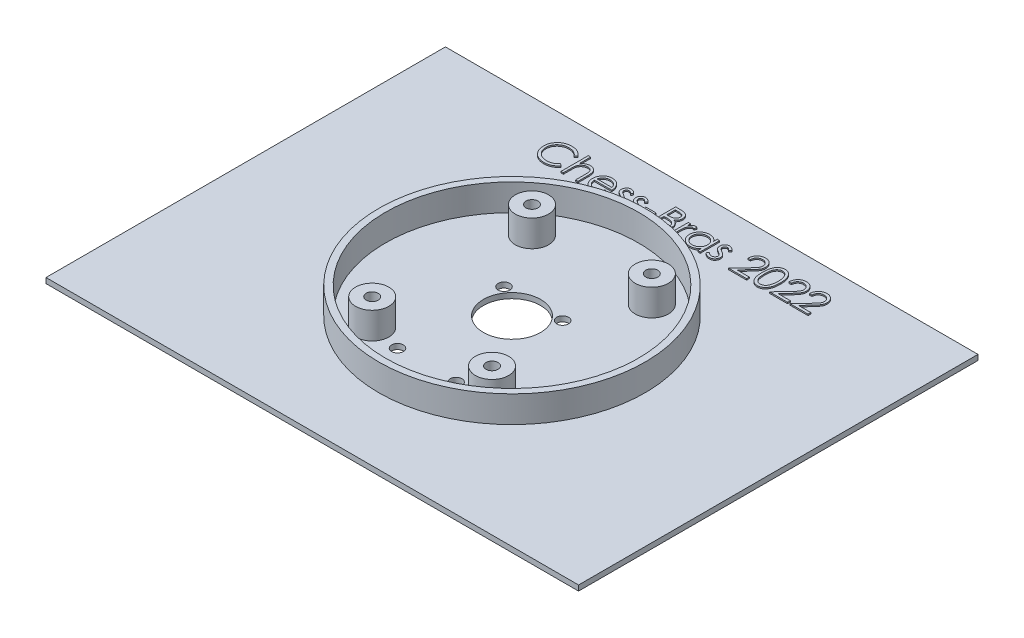
SolidWorks part; units mm, degrees
ref_plane "Plan de face" through (0, 0, 0) normal (0, 0, 1) x (1, 0, 0)
ref_plane "Plan de dessus" through (0, 0, 0) normal (0, 1, 0) x (1, 0, 0)
ref_plane "Plan de droite" through (0, 0, 0) normal (1, 0, 0) x (0, 0, -1)
sketch "Esquisse1" plane through (0, 0, 0) normal (0, 1, 0) x (1, 0, 0)
  line L1 (-90, -90) -> (90, -90) construction
  line L2 (-90, -90) -> (-90, 90) construction
  line L3 (-90, 90) -> (90, 90) construction
  line L4 (90, -90) -> (90, 90) construction
  line L5 (-90, -90) -> (90, 90) construction
  line L6 (-90, 90) -> (90, -90) construction
  point P0 (0, 0)
  dimension "D1" = 180
  dimension "D2" = 180
sketch "Esquisse2" plane through (0, 0, 0) normal (0, 1, 0) x (1, 0, 0)
  line L1 (-100, -75) -> (100, -75)
  line L2 (-100, -75) -> (-100, 75)
  line L3 (-100, 75) -> (100, 75)
  line L4 (100, -75) -> (100, 75)
  line L5 (-100, -75) -> (100, 75) construction
  line L6 (-100, 75) -> (100, -75) construction
  point P0 (0, 0)
  dimension "D1" = 200
  dimension "D2" = 150
extrude "Boss.-Extru.1" add sketch "Esquisse2" along normal blind 1
sketch "Esquisse3" plane through (0, 1, 0) normal (0, 1, 0) x (1, 0, 0)
  line L4 (100, -75) -> (100, 75)
  line L5 (100, 75) -> (-100, 75)
  line L6 (-100, 75) -> (-100, -75)
  line L7 (-100, -75) -> (100, -75)
  line L8 (100, -75) -> (100, 75)
  line L9 (100, 75) -> (-100, 75)
  line L10 (-100, 75) -> (-100, -75)
  line L11 (-100, -75) -> (100, -75)
  line L12 (7.5, 59.5294) -> (7.5, 65)
  line L13 (90, 65) -> (7.5, 65)
  line L16 (-90, 65) -> (-90, 7.5)
  line L17 (-90, -65) -> (-7.5, -65)
  line L18 (90, -65) -> (90, -7.5)
  line L19 (0, 42.5) -> (0, 65) construction
  line L20 (-7.5, 59.5294) -> (-7.5, 65)
  line L39 (-7.5, 42.5) -> (-7.5, 65) construction
  line L40 (7.5, 42.5) -> (7.5, 65) construction
  line L41 (-90, 0) -> (90, 0) construction
  line L42 (-7.5, 65) -> (-90, 65)
  line L43 (90, 65) -> (-90, 65) construction
  line L45 (-90, -7.5) -> (-59.5294, -7.5)
  line L46 (-90, 7.5) -> (-59.5294, 7.5)
  line L47 (-90, -7.5) -> (-90, -65)
  line L48 (-90, 65) -> (-90, -65) construction
  line L51 (-90, 7.5) -> (90, 7.5) construction
  line L52 (59.5294, -7.5) -> (90, -7.5)
  line L53 (-90, -7.5) -> (90, -7.5) construction
  line L54 (59.5294, 7.5) -> (90, 7.5)
  line L55 (90, 7.5) -> (90, 65)
  line L56 (90, -65) -> (90, 65) construction
  line L57 (0, 0) -> (0, -75) construction
  line L58 (-7.5, -59.5294) -> (-7.5, -65)
  line L59 (7.5, -65) -> (90, -65)
  line L60 (-7.5, 0) -> (-7.5, -75) construction
  line L62 (7.5, -59.5294) -> (7.5, -65)
  line L63 (-90, -65) -> (90, -65) construction
  arc A0 (59.5294, 7.5) -> (7.5, 59.5294) centre (0, 0) ccw
  arc A1 (-7.5, 59.5294) -> (-59.5294, 7.5) centre (0, 0) ccw
  arc A2 (-59.5294, -7.5) -> (-7.5, -59.5294) centre (0, 0) ccw
  arc A3 (7.5, -59.5294) -> (59.5294, -7.5) centre (0, 0) ccw
  point P8 (0, 0)
  point P39 (0, 0)
  dimension "D10" = 120
  dimension "D5" = 7.5
  dimension "D6" = 7.5
  dimension "D9" = 0
  dimension "D1" = 0
  dimension "D2" = 10
  dimension "D7" = 7.5
  dimension "D8" = 7.5
extrude "Boss.-Extru.2" add sketch "Esquisse3" along normal blind 1
sketch "Esquisse21" plane through (0, 2, 0) normal (0, 1, 0) x (1, 0, 0)
  line L0 (0, 38.0247) -> (0, -27.9888) construction
  line L1 (31.0483, 0) -> (-33.3119, 0) construction
  circle A0 centre (-22.5, 30) radius 6.25
  circle A1 centre (-22.5, -30) radius 6.25
  circle A3 centre (22.5, 30) radius 6.25
  circle A5 centre (22.5, -30) radius 6.25
  dimension "D3" = 12.5
  dimension "D1" = 22.5
  dimension "D2" = 30
extrude "Boss.-Extru.6" add sketch "Esquisse21" along normal blind 10
hole_wizard "Chambrage pour vis à tête cylindrique à 6 pans creux (ou vis CHC) M21" positions "Esquisse7" profile "Esquisse8" counterbore size "M2" standard "Ansi Metric" end condition through all
sketch "Esquisse7" plane through (0, 0, 0) normal (0, -1, 0) x (-1, 0, 0)
  line L0 (-19.1786, -12) -> (19.1786, -12) construction
  line L2 (0, -21.3375) -> (0, 18.8747) construction
  point P9 (-11, -32)
  point P22 (11, -32)
  point P24 (-11, 8)
  point P25 (11, 8)
  point P26 (0, -12)
  dimension "D1" = 11
  dimension "D2" = 20
  dimension "D3" = 8
sketch "Esquisse8" plane through (-11, 0, -8) normal (1, 0, 0) x (0, 0, -1)
  line L0 (0, 0) -> (0, 12)
  line L1 (0, 12) -> (1.2, 12)
  line L3 (1.2, 12) -> (1.2, 3.5)
  line L4 (1.2, 3.5) -> (2.2, 3.5)
  line L5 (2.2, 3.5) -> (2.2, 0)
  line L7 (2.2, 0) -> (0, 0)
  line L11 (0, -6.35) -> (0, 107.95) construction
  dimension "Diamètre du perçage jusqu'au prochain" = 2.4
  dimension "Profondeur du perçage jusqu'au prochain" = 12
  dimension "Diamètre du chambrage" = 4.4
  dimension "Profondeur du chambrage" = 3.5
hole_wizard "Chambrage pour vis à tête cylindrique à 6 pans creux (ou vis CHC) M41" positions "Esquisse12" profile "Esquisse13" counterbore size "M4" standard "Ansi Metric" end condition through all
sketch "Esquisse12" plane through (0, 0, 0) normal (0, -1, 0) x (-1, 0, 0)
  line L0 (-30.249, 0) -> (45.5995, 0) construction
  line L2 (0, 38.4688) -> (0, -28.5023) construction
  point P0 (22.5, 30)
  point P4 (22.5, -30)
  point P17 (-22.5, 30)
  point P19 (-22.5, -30)
  dimension "D1" = 22.5
  dimension "D2" = 30
sketch "Esquisse13" plane through (-22.5, 0, -30) normal (1, 0, 0) x (0, 0, -1)
  line L0 (0, 0) -> (0, 12)
  line L1 (0, 12) -> (2.25, 12)
  line L3 (2.25, 12) -> (2.25, 5)
  line L4 (2.25, 5) -> (4, 5)
  line L5 (4, 5) -> (4, 0)
  line L7 (4, 0) -> (0, 0)
  line L11 (0, -6.35) -> (0, 107.95) construction
  dimension "Diamètre du perçage jusqu'au prochain" = 4.5
  dimension "Profondeur du perçage jusqu'au prochain" = 12
  dimension "Diamètre du chambrage" = 8
  dimension "Profondeur du chambrage" = 5
sketch "Esquisse15" plane through (0, 2, 0) normal (0, 1, 0) x (1, 0, 0)
  circle A0 centre (0, 0) radius 10.75
  dimension "D1" = 21.5
extrude "Enlèv. mat.-Extru.2" cut sketch "Esquisse15" against normal through all
sketch "Esquisse22" plane through (0, 2, 0) normal (0, 1, 0) x (1, 0, 0)
  circle A0 centre (0, 0) radius 50
  circle A1 centre (0, 0) radius 47.5
  dimension "D1" = 100
  dimension "D2" = 95
extrude "Boss.-Extru.7" add sketch "Esquisse22" along normal blind 10
sketch "Esquisse23" plane through (0, 1, 0) normal (0, 1, 0) x (1, 0, 0)
  line L0 (-90, -7.5) -> (-59.5294, -7.5)
  line L1 (-7.5, -59.5294) -> (-7.5, -65)
  line L2 (-7.5, -65) -> (-90, -65)
  line L3 (-90, -65) -> (-90, -7.5)
  line L4 (7.5, -59.5294) -> (7.5, -65)
  line L5 (7.5, -65) -> (90, -65)
  line L6 (90, -65) -> (90, -7.5)
  line L7 (90, -7.5) -> (59.5294, -7.5)
  line L8 (-7.5, 59.5294) -> (-7.5, 65)
  line L9 (-7.5, 65) -> (-90, 65)
  line L10 (-90, 65) -> (-90, 7.5)
  line L11 (-90, 7.5) -> (-59.5294, 7.5)
  line L12 (7.5, 59.5294) -> (7.5, 65)
  line L13 (7.5, 65) -> (90, 65)
  line L14 (90, 65) -> (90, 7.5)
  line L15 (90, 7.5) -> (59.5294, 7.5)
  arc A0 (-59.5294, -7.5) -> (-7.5, -59.5294) centre (0, 0) ccw
  arc A1 (59.5294, -7.5) -> (7.5, -59.5294) centre (0, 0) cw
  arc A2 (-59.5294, 7.5) -> (-7.5, 59.5294) centre (0, 0) cw
  arc A3 (59.5294, 7.5) -> (7.5, 59.5294) centre (0, 0) ccw construction
  arc A6 (7.5, 59.5294) -> (59.5294, 7.5) centre (0, 0) cw
  point P45 (7.5, 7.7015)
  point P46 (7.5, 7.5)
  point P47 (7.5, 7.5)
  point P48 (0, 0)
  point P49 (59.5294, 7.5)
  point P50 (4.957, 4.957)
  point P51 (4.957, 4.957)
  point P52 (0, 0)
extrude "Boss.-Extru.8" add sketch "Esquisse23" along normal blind 1
sketch "Esquisse24" plane through (0, 2, 0) normal (0, 1, 0) x (1, 0, 0)
  text T0 "Chess-Bras 2022" font "Century Gothic" height 10
extrude "Boss.-Extru.10" add sketch "Esquisse24" along normal blind 0.5
